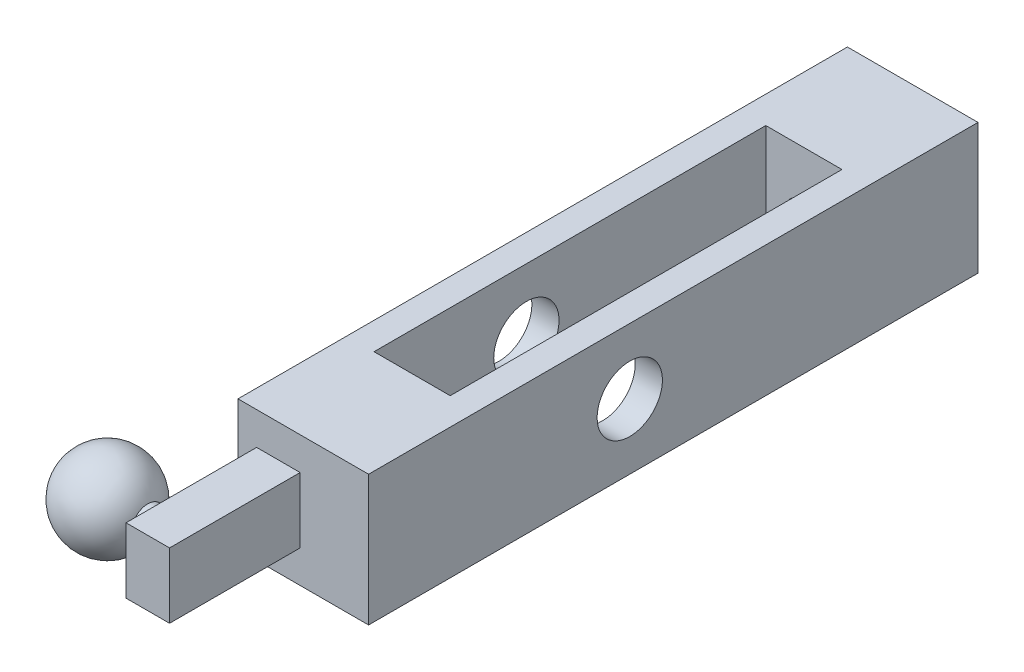
SolidWorks part; units mm, degrees
ref_plane "前视基准面" through (0, 0, 0) normal (0, 0, 1) x (1, 0, 0)
ref_plane "上视基准面" through (0, 0, 0) normal (0, 1, 0) x (1, 0, 0)
ref_plane "右视基准面" through (0, 0, 0) normal (1, 0, 0) x (0, 0, -1)
other "Configuration Table"
sketch "草图1" plane through (0, 0, 0) normal (0, 0, 1) x (1, 0, 0)
  line L1 (3, -3) -> (-3, -3)
  line L2 (3, -3) -> (3, 3)
  line L3 (3, 3) -> (-3, 3)
  line L4 (-3, -3) -> (-3, 3)
  line L5 (3, -3) -> (-3, 3) construction
  line L6 (3, 3) -> (-3, -3) construction
  point P0 (0, 0)
  dimension "D1" = 6
  dimension "D2" = 6
extrude "凸台-拉伸1" add sketch "草图1" along normal blind 28
sketch "草图2" plane through (0, 0, 28) normal (0, 0, 1) x (1, 0, 0)
  line L1 (-2.1448, 1.4955) -> (-0.1448, 1.4955)
  line L2 (-2.1448, 1.4955) -> (-2.1448, -1.5045)
  line L3 (-2.1448, -1.5045) -> (-0.1448, -1.5045)
  line L4 (-0.1448, 1.4955) -> (-0.1448, -1.5045)
  line L5 (-2.1448, 1.4955) -> (-0.1448, -1.5045) construction
  line L6 (-2.1448, -1.5045) -> (-0.1448, 1.4955) construction
  point P0 (-1.1448, -0.0045)
  dimension "D1" = 2
  dimension "D2" = 3
extrude "凸台-拉伸2" add sketch "草图2" along normal blind 6
sketch "草图3" plane through (-2.1448, 0, 0) normal (-1, 0, 0) x (0, 0, 1)
  circle A0 centre (32, 0) radius 0.75
  dimension "D1" = 1.5
  dimension "D2" = 32
extrude "凸台-拉伸3" add sketch "草图3" along normal blind 1
sketch "草图4" plane through (0, 0, 0) normal (0, 1, 0) x (1, 0, 0)
  line L0 (-3.1448, -32) -> (-6.9988, -32)
  line L1 (-3.1448, -31.25) -> (-3.1448, -32.75) construction
  line L2 (-3.1448, -32) -> (-3.1448, -31.25)
  arc A0 (-3.1448, -31.25) -> (-6.9988, -32) centre (-4.9988, -32) ccw
  dimension "D1" = 4
revolve "旋转1" add sketch "草图4" angle 360 about L0
sketch "草图5" plane through (0.5, 3, 0) normal (0, -1, 0) x (0, 0, 1)
  line L0 (28, 3.5) -> (0, 3.5) construction
  line L1 (5, 2.25) -> (23, 2.25)
  line L2 (5, 2.25) -> (5, -1.25)
  line L3 (5, -1.25) -> (23, -1.25)
  line L4 (23, 2.25) -> (23, -1.25)
  point P4 (5, 0.5)
  point P8 (14, 3.5)
  point P9 (14, 2.25)
  dimension "D1" = 18
  dimension "D2" = 3.5
extrude "切除-拉伸1" cut sketch "草图5" along normal blind 8
sketch "草图6" plane through (-3, 0, 0) normal (-1, 0, 0) x (0, 0, 1)
  line L0 (0, 3) -> (0, -3) construction
  circle A0 centre (16, 0) radius 1.5
  dimension "D1" = 3
  dimension "D2" = 16
extrude "切除-拉伸2" cut sketch "草图6" against normal blind 8
sketch "草图7" plane through (0, 0, 0) normal (0, 0, -1) x (-1, 0, 0)
  circle A0 centre (0, 0) radius 0.9
  dimension "D1" = 1.8
extrude "切除-拉伸3" cut sketch "草图7" against normal blind 8
